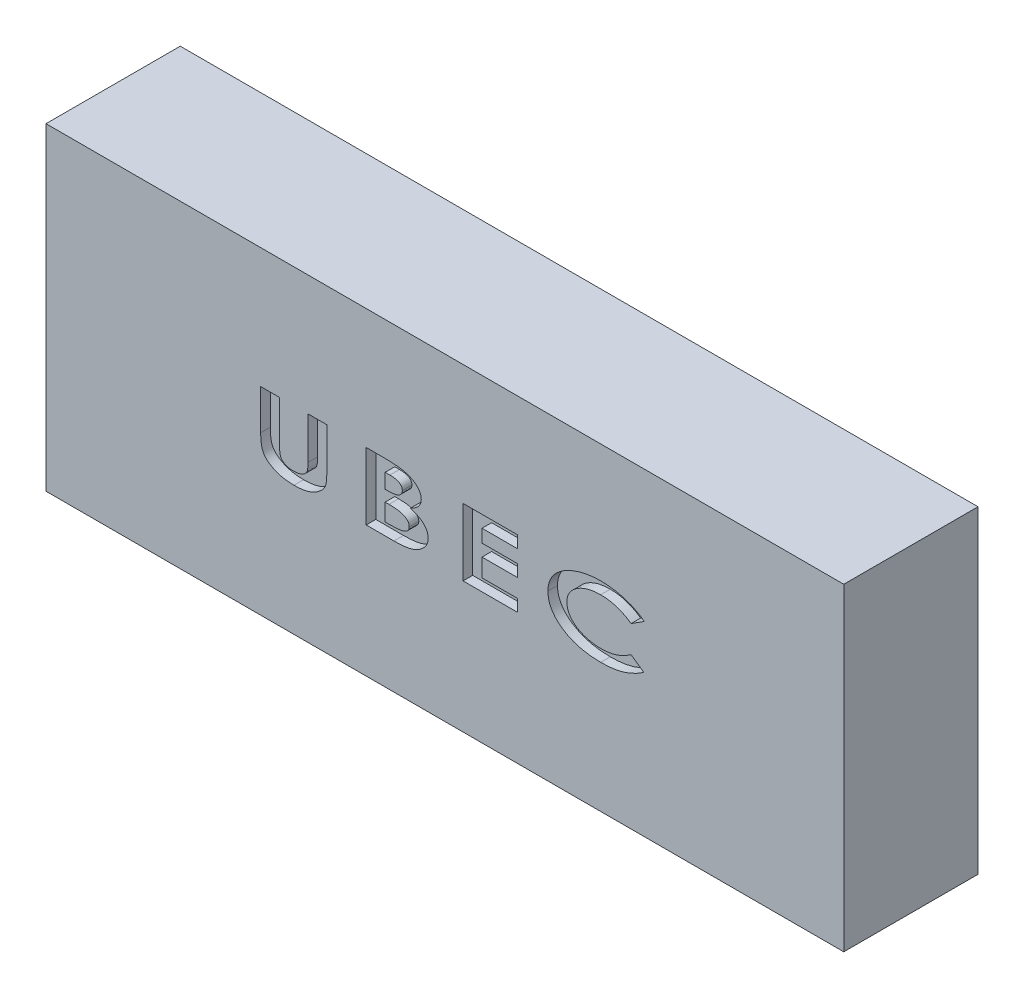
SolidWorks part; units mm, degrees
ref_plane "Plano frontal" through (0, 0, 0) normal (0, 0, 1) x (1, 0, 0)
ref_plane "Plano superior" through (0, 0, 0) normal (0, 1, 0) x (1, 0, 0)
ref_plane "Plano direito" through (0, 0, 0) normal (1, 0, 0) x (0, 0, -1)
sketch "Esboço1" plane through (0, 0, 0) normal (0, 0, 1) x (1, 0, 0)
  line L1 (-20.8, 8.3) -> (20.8, 8.3)
  line L2 (-20.8, 8.3) -> (-20.8, -8.3)
  line L3 (-20.8, -8.3) -> (20.8, -8.3)
  line L4 (20.8, 8.3) -> (20.8, -8.3)
  line L5 (-20.8, 8.3) -> (20.8, -8.3) construction
  line L6 (-20.8, -8.3) -> (20.8, 8.3) construction
  point P0 (0, 0)
  dimension "D1" = 41.6
  dimension "D2" = 16.6
extrude "Ressalto-extrusão1" add sketch "Esboço1" along normal blind 7
sketch "Esboço2" plane through (0, 0, 7) normal (0, 0, 1) x (1, 0, 0)
  text T0 "<b>UBEC</b>" font "Century Gothic" height 3.5
extrude "Corte-extrusão1" cut sketch "Esboço2" against normal blind 0.5
